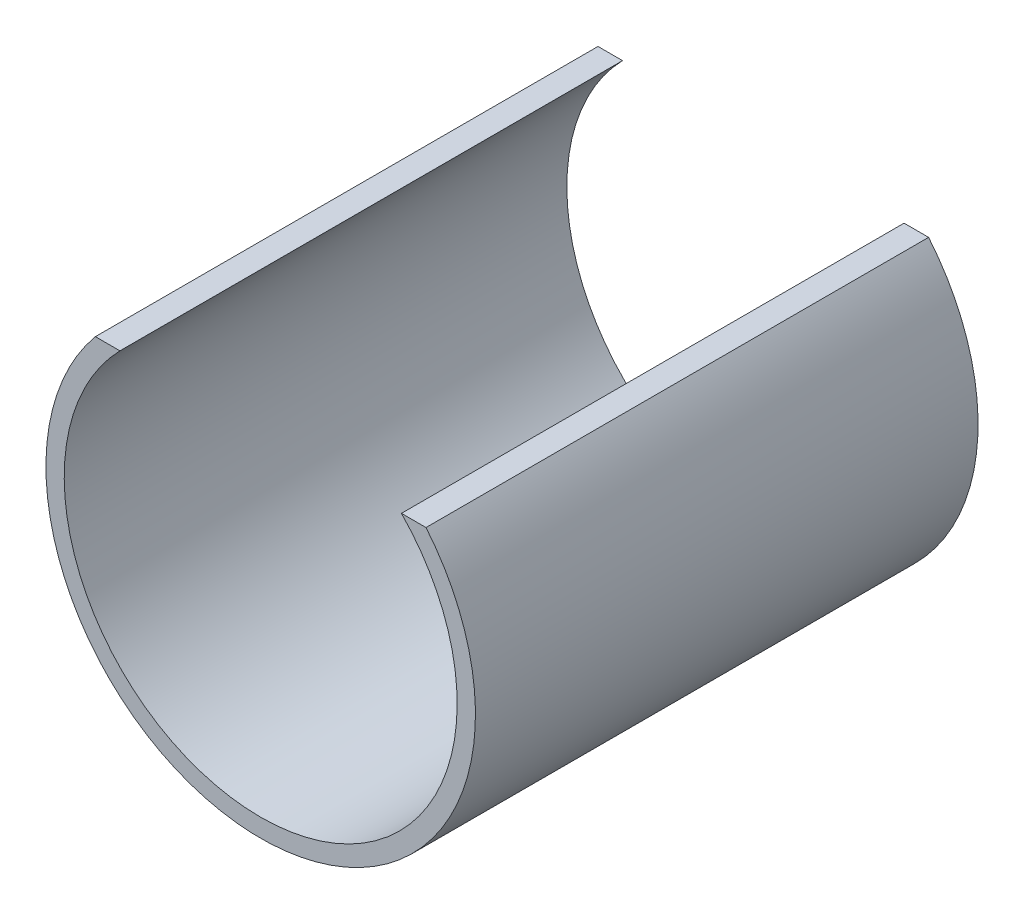
SolidWorks part; units mm, degrees
ref_plane "Front Plane" through (0, 0, 0) normal (0, 0, 1) x (1, 0, 0)
ref_plane "Top Plane" through (0, 0, 0) normal (0, 1, 0) x (1, 0, 0)
ref_plane "Right Plane" through (0, 0, 0) normal (1, 0, 0) x (0, 0, -1)
sketch "Sketch2" plane through (0, 0, 0) normal (0, 0, 1) x (1, 0, 0)
  line L0 (1.5403, 1.5) -> (1.809, 1.5)
  line L2 (1.809, 1.5) -> (1.5403, 1.5)
  line L3 (-1.5403, 1.5) -> (-1.809, 1.5)
  arc A0 (-1.5403, 1.5) -> (1.5403, 1.5) centre (0, 0) ccw
  arc A1 (-1.809, 1.5) -> (1.809, 1.5) centre (0, 0) ccw
  dimension "D1" = 4.3
  dimension "D2" = 4.7
extrude "Boss-Extrude1" add sketch "Sketch2" against normal up to surface (5.5 mm away) contours L3 A1 L0 A0
